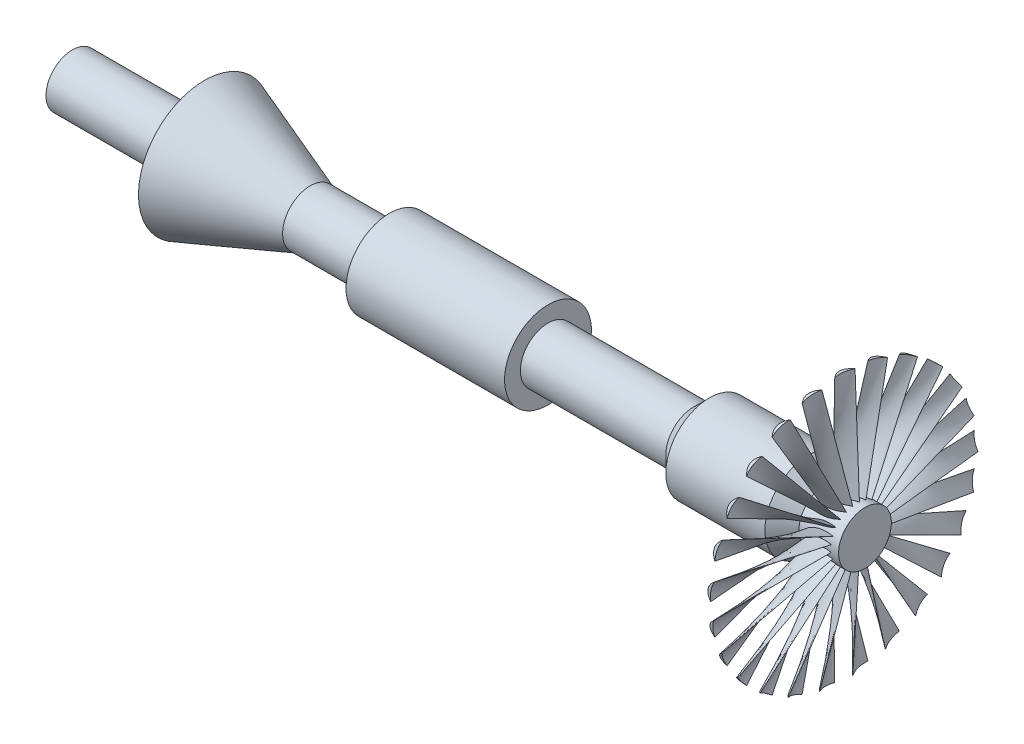
SolidWorks part; units mm, degrees
ref_plane "Front Plane" through (0, 0, 0) normal (0, 0, 1) x (1, 0, 0)
ref_plane "Top Plane" through (0, 0, 0) normal (0, 1, 0) x (1, 0, 0)
ref_plane "Right Plane" through (0, 0, 0) normal (1, 0, 0) x (0, 0, -1)
sketch "Sketch1" plane through (0, 0, 0) normal (0, 0, 1) x (1, 0, 0)
  line L0 (-300, 0) -> (300, 0)
  line L1 (-300, 0) -> (-300, 20)
  line L2 (-300, 20) -> (-200, 20)
  line L3 (-200, 20) -> (-200, 50)
  line L4 (-200, 50) -> (-120, 20.8824)
  line L5 (-120, 20.8824) -> (-60, 20.8824)
  line L6 (-60, 20.8824) -> (-60, 32.8824)
  line L7 (-60, 32.8824) -> (60, 32.8824)
  line L8 (60, 32.8824) -> (60, 20.8824)
  line L9 (60, 20.8824) -> (170.1176, 20.8824)
  line L10 (170.1176, 20.8824) -> (182.1176, 32.8824)
  line L11 (182.1176, 32.8824) -> (257.1176, 32.8824)
  line L12 (257.1176, 32.8824) -> (270, 20)
  line L13 (270, 20) -> (300, 20)
  line L14 (300, 20) -> (300, 0)
  line L15 (182.1176, 32.8824) -> (-251.5152, 32.8824) construction
  point P0 (0, 32.8824)
  point P4 (0, 0)
  dimension "D1" = 600
  dimension "D2" = 20
  dimension "D3" = 100
  dimension "D4" = 30
  dimension "D5" = 70
  dimension "D6" = 80
  dimension "D7" = 60
  dimension "D8" = 20
  dimension "D9" = 30
  dimension "D10" = 135
  dimension "D11" = 135
  dimension "D12" = 12
  dimension "D13" = 120
  dimension "D14" = 75
  dimension "D15" = 110.1176
revolve "Revolve1" add sketch "Sketch1" angle 360 about L0
sketch "Sketch2" plane through (0, 0, 0) normal (0, 1, 0) x (1, 0, 0)
  line L0 (300, 0) -> (270, 0) construction
  line L1 (300, -20) -> (300, 20) construction
  line L2 (270, -20) -> (270, 20) construction
  spline S0 degree 2 poles (275.2786, 0) (285.909, 3.4343) (296.5978, 0) knots 0 0 0 1 1 1
  spline S1 degree 2 poles (275.2786, 0) (285.909, -3.4343) (296.5978, 0) knots 0 0 0 1 1 1
  point P8 (285.3603, 1.7124)
ref_plane "Plane1" through (0, 100, 0) normal (0, 1, 0) x (1, 0, 0)
sketch "Sketch3" plane through (0, 100, 0) normal (0, 1, 0) x (1, 0, 0)
  line L0 (300, 0) -> (270, 0) construction
  spline S0 degree 2 poles (285.2971, 7.1683) (281.8787, 0.7508) (283.399, -6.2821) knots 0 0 0 1 1 1
  spline S1 degree 2 poles (285.2971, 7.1683) (277.536, 1.0265) (283.399, -6.2821) knots 0 0 0 1 1 1
  point P4 (283.399, -6.2821)
  point P5 (0, 0)
sketch3d "3DSketch1"
  spline S0 degree 2 poles (283.399, 100, 6.2821) (279.884, 49.6538, 8.6414) (275.2786, 0, 0) knots 0 0 0 1 1 1
  spline S1 degree 2 poles (285.2971, 100, -7.1683) (274.3849, 45.8908, -14.6175) (296.5978, 0, 0) knots 0 0 0 1 1 1
loft "Loft1" add profiles "Sketch3", "Sketch2"
pattern_circular "CirPattern1" count 25 over 360 about axis through (300, 0, 0) along (-1, 0, 0) of "Loft1"
